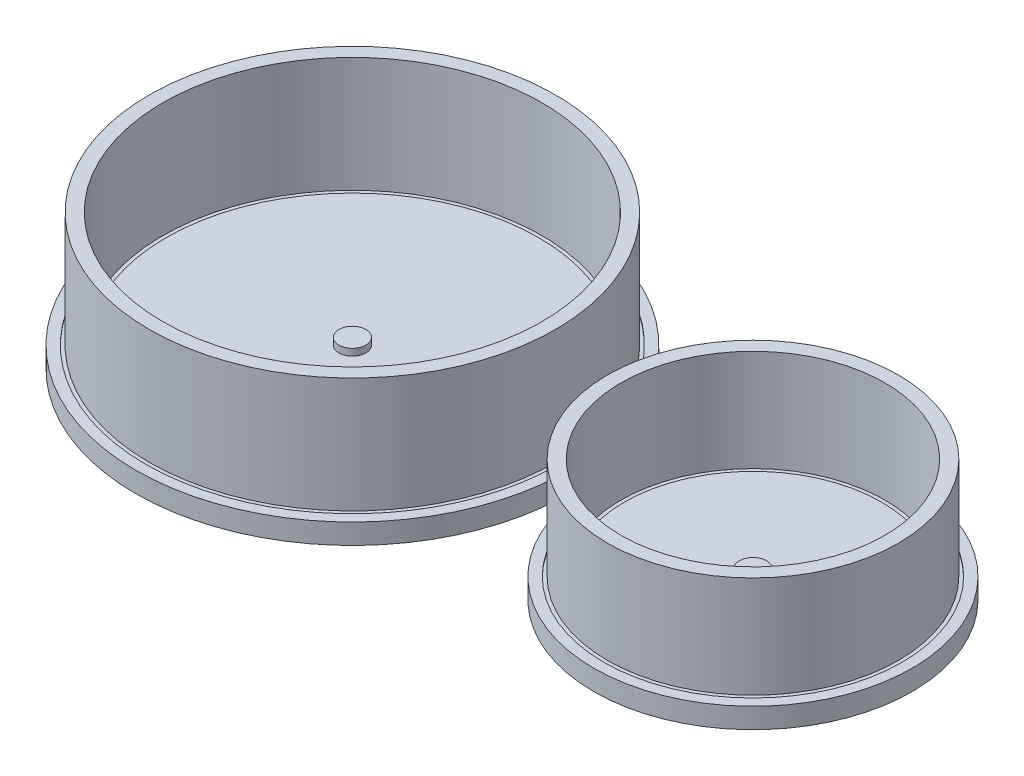
SolidWorks part; units mm, degrees
ref_plane "Спереди" through (0, 0, 0) normal (0, 0, 1) x (1, 0, 0)
ref_plane "Сверху" through (0, 0, 0) normal (0, 1, 0) x (1, 0, 0)
ref_plane "Справа" through (0, 0, 0) normal (1, 0, 0) x (0, 0, -1)
sketch "Эскиз1" plane through (0, 0, 0) normal (0, 1, 0) x (1, 0, 0)
  line L0 (0, 23) -> (0, 32) construction
  line L5 (0, 0) -> (59.1498, 0) construction
  circle A0 centre (0, 0) radius 23 construction
  circle A1 centre (0, 0) radius 32
  circle A3 centre (59.1498, 0) radius 14.5 construction
  circle A4 centre (59.1498, 0) radius 23.5
  point P9 (59.1498, 0)
  dimension "D1" = 46
  dimension "D2" = 9
  dimension "D3" = 9
  dimension "D4" = 29
  dimension "D5" = 9
extrude "Бобышка-Вытянуть2" add sketch "Эскиз1" along normal blind 3
sketch "Эскиз5" plane through (0, 3, 0) normal (0, 1, 0) x (1, 0, 0)
  circle A0 centre (0, 0) radius 30.5
  circle A1 centre (0, 0) radius 27.5
  circle A2 centre (0, 0) radius 32 construction
  circle A3 centre (59.1498, 0) radius 22
  circle A4 centre (59.1498, 0) radius 19
  circle A5 centre (59.1498, 0) radius 23.5 construction
  dimension "D1" = 3
  dimension "D2" = 1.5
  dimension "D3" = 3
  dimension "D4" = 1.5
extrude "Вырез-Вытянуть2" cut sketch "Эскиз5" against normal blind 0.2
sketch "Эскиз6" plane through (0, 3, 0) normal (0, 1, 0) x (1, 0, 0)
  circle A0 centre (0, 0) radius 30
  circle A1 centre (0, 0) radius 28
  circle A2 centre (0, 0) radius 32 construction
  circle A3 centre (59.1498, 0) radius 19.5
  circle A4 centre (59.1498, 0) radius 21.5
  circle A5 centre (59.1498, 0) radius 23.5 construction
  dimension "D1" = 2
  dimension "D2" = 2
  dimension "D3" = 2
  dimension "D4" = 2
extrude "Бобышка-Вытянуть5" add sketch "Эскиз6" along normal blind 17 separate body
sketch "Эскиз7" plane through (0, 3, 0) normal (0, 1, 0) x (1, 0, 0)
  circle A0 centre (0, 0) radius 2
  circle A1 centre (59.1498, 0) radius 2
  dimension "D1" = 4
extrude "Бобышка-Вытянуть6" add sketch "Эскиз7" along normal blind 1
sketch "Эскиз9" plane through (0, 20, 0) normal (0, 1, 0) x (1, 0, 0)
  circle A0 centre (59.1498, 0) radius 24.4303
extrude "Вырез-Вытянуть3" cut sketch "Эскиз9" against normal blind 2
